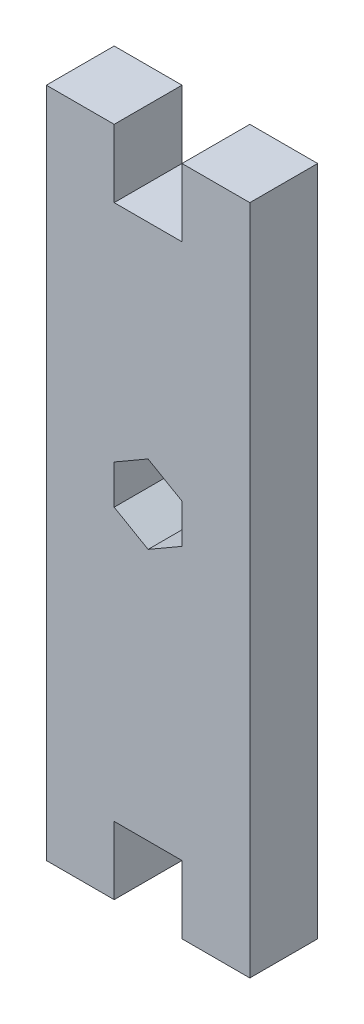
SolidWorks part; units mm, degrees
ref_plane "Plan de face" through (0, 0, 0) normal (0, 0, 1) x (1, 0, 0)
ref_plane "Plan de dessus" through (0, 0, 0) normal (0, 1, 0) x (1, 0, 0)
ref_plane "Plan de droite" through (0, 0, 0) normal (1, 0, 0) x (0, 0, -1)
sketch "Esquisse1" plane through (0, 0, 0) normal (0, 0, 1) x (1, 0, 0)
  line L0 (3.4681, 2.9254) -> (8.4681, 2.9254)
  line L1 (-6.5319, 2.9254) -> (-1.5319, 2.9254)
  line L2 (-6.5319, 2.9254) -> (-6.5319, -46.5746)
  line L3 (-6.5319, -46.5746) -> (-1.5319, -46.5746)
  line L4 (8.4681, 2.9254) -> (8.4681, -46.5746)
  line L6 (-1.5319, 2.9254) -> (-1.5319, -2.0746)
  line L7 (-1.5319, -2.0746) -> (3.4681, -2.0746)
  line L8 (3.4681, 2.9254) -> (3.4681, -2.0746)
  line L10 (3.4681, -46.5746) -> (3.4681, -41.5746)
  line L11 (-1.5319, -41.5746) -> (3.4681, -41.5746)
  line L12 (-1.5319, -46.5746) -> (-1.5319, -41.5746)
  line L13 (3.4681, -46.5746) -> (8.4681, -46.5746)
  dimension "D1" = 15
  dimension "D2" = 49.5
  dimension "D3" = 5
  dimension "D5" = 5
extrude "Boss.-Extru.1" add sketch "Esquisse1" along normal blind 5
sketch "Esquisse2" plane through (0, 0, 0) normal (0, 0, -1) x (-1, 0, 0)
  line L1 (-3.4681, -21.5179) -> (-0.9681, -22.9613)
  line L2 (-0.9681, -22.9613) -> (1.5319, -21.5179)
  line L3 (1.5319, -21.5179) -> (1.5319, -18.6312)
  line L4 (1.5319, -18.6312) -> (-0.9681, -17.1878)
  line L5 (-0.9681, -17.1878) -> (-3.4681, -18.6312)
  line L6 (-3.4681, -18.6312) -> (-3.4681, -21.5179)
  circle A0 centre (-0.9681, -20.0746) radius 2.5 construction
  dimension "D1" = 5
extrude "Cut-Extrude1" cut sketch "Esquisse2" against normal blind 10
